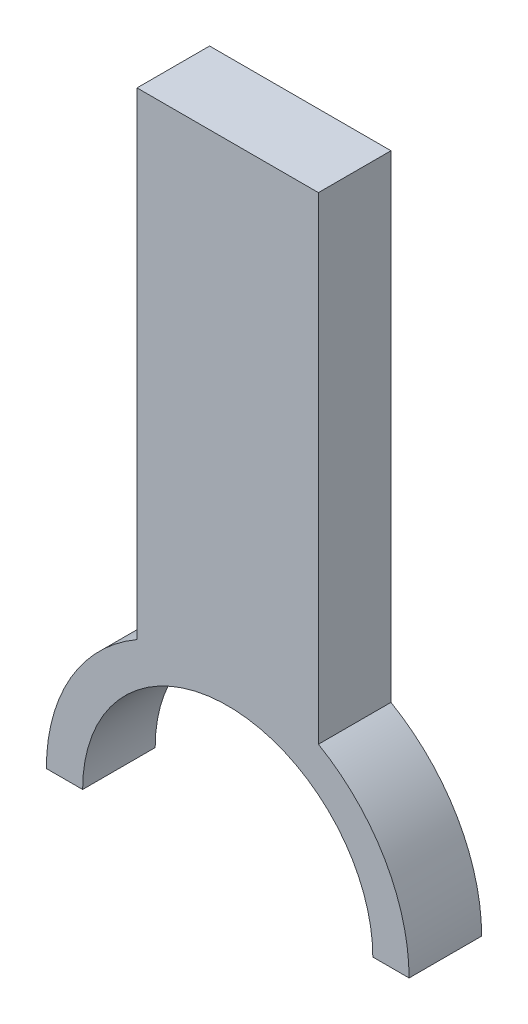
SolidWorks part; units mm, degrees
ref_plane "Front Plane" through (0, 0, 0) normal (0, 0, 1) x (1, 0, 0)
ref_plane "Top Plane" through (0, 0, 0) normal (0, 1, 0) x (1, 0, 0)
ref_plane "Right Plane" through (0, 0, 0) normal (1, 0, 0) x (0, 0, -1)
sketch "Sketch1" plane through (0, 0, 0) normal (0, 0, 1) x (1, 0, 0)
  line L0 (10, 0) -> (8, 0)
  line L1 (0, 0) -> (1.1314, 7.9196) construction
  line L2 (-5, -35) -> (5, -35)
  line L3 (-5, 8.6603) -> (-5, 35)
  line L4 (-5, 35) -> (5, 35)
  line L5 (5, 8.6603) -> (5, 35)
  line L6 (-1.4142, -9.8995) -> (-1.1314, -7.9196) construction
  line L7 (-1.1314, 7.9196) -> (0, 0) construction
  line L8 (-8, 0) -> (-10, 0)
  arc A0 (-5, 8.6603) -> (-10, 0) centre (0, 0) ccw
  arc A1 (-1.1314, -7.9196) -> (1.1314, -7.9196) centre (0, 0) ccw
  arc A2 (8, 0) -> (-8, 0) centre (0, 0) ccw
  arc A3 (10, 0) -> (5, 8.6603) centre (0, 0) ccw
  dimension "D2" = 16
  dimension "D3" = 10
  dimension "D4" = 70
extrude "Boss-Extrude1" add sketch "Sketch1" along normal blind 4 contours L0 A3 L5 L4 L3 A0 L8 A2
